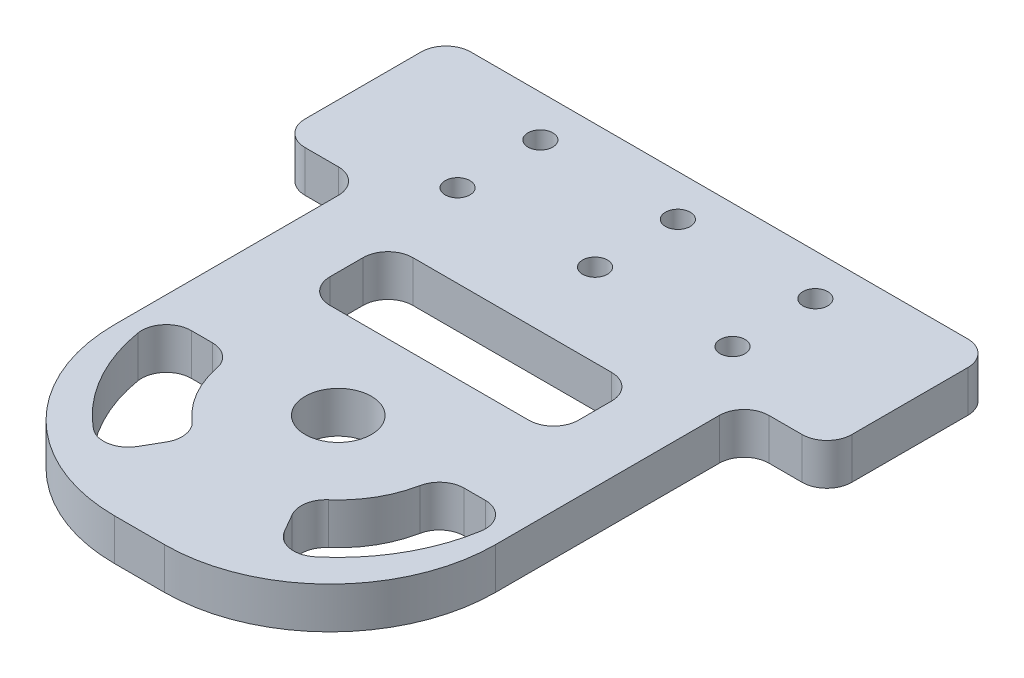
SolidWorks part; units mm, degrees
material "Thornel Mat VMA"
ref_plane "前视基准面" through (0, 0, 0) normal (0, 0, 1) x (1, 0, 0)
ref_plane "上视基准面" through (0, 0, 0) normal (0, 1, 0) x (1, 0, 0)
ref_plane "右视基准面" through (0, 0, 0) normal (1, 0, 0) x (0, 0, -1)
sketch "草图1" plane through (0, 0, 0) normal (0, 1, 0) x (1, 0, 0)
  line L1 (-23, -35) -> (23, -35)
  line L2 (-23, -35) -> (-23, 35)
  line L3 (-23, 35) -> (23, 35)
  line L4 (23, -35) -> (23, 35)
  line L5 (-23, -35) -> (23, 35) construction
  line L6 (-23, 35) -> (23, -35) construction
  point P0 (0, 0)
  dimension "D1" = 46
  dimension "D2" = 70
extrude "凸台-拉伸1" add sketch "草图1" along normal blind 5
sketch "草图2" plane through (0, 0, 0) normal (0, -1, 0) x (1, 0, 0)
  line L0 (23, -35) -> (-23, -35) construction
  circle A0 centre (0, 11) radius 4
  dimension "D2" = 8
  dimension "D1" = 46
extrude "切除-拉伸1" cut sketch "草图2" against normal through all
fillet "圆角1" radius 20 2 edges at (23, 2.5, 35) (-23, 2.5, 35)
sketch "草图6" plane through (0, 0, 0) normal (0, -1, 0) x (1, 0, 0)
  line L0 (23, -35) -> (-23, -35) construction
  line L7 (0, 7) -> (0, -35) construction
  line L8 (12.5, 11) -> (21, 11)
  line L9 (-12.5, 11) -> (-21, 11)
  line L10 (6.25, 21.8253) -> (10.5, 29.1865)
  line L11 (-6.25, 21.8253) -> (-10.5, 29.1865)
  circle A0 centre (0, 11) radius 4 construction
  arc A2 (12.5, 11) -> (6.25, 21.8253) centre (0, 11) ccw
  arc A3 (-6.25, 21.8253) -> (-12.5, 11) centre (0, 11) ccw
  arc A4 (21, 11) -> (10.5, 29.1865) centre (0, 11) ccw
  arc A5 (-10.5, 29.1865) -> (-21, 11) centre (0, 11) ccw
  point P0 (0, -14)
  dimension "D4" = 25
  dimension "D5" = 60
extrude "切除-拉伸4" cut sketch "草图6" against normal through all
fillet "圆角3" radius 3 8 edges at (21, 2.5, 11) (12.5, 2.5, 11) (6.25, 2.5, 21.8253) (10.5, 2.5, 29.1865) (-6.25, 2.5, 21.8253) (-10.5, 2.5, 29.1865) (-21, 2.5, 11) (-12.5, 2.5, 11)
sketch "草图8" plane through (23, 0, 0) normal (1, 0, 0) x (0, 0, -1)
  line L0 (-15, 5) -> (35, 5) construction
  line L1 (35, 0) -> (15, 0)
  line L2 (35, 0) -> (35, 5)
  line L3 (35, 5) -> (15, 5)
  line L4 (15, 0) -> (15, 5)
  dimension "D1" = 20
extrude "凸台-拉伸2" add sketch "草图8" along normal blind 10
sketch "草图9" plane through (-23, 0, 0) normal (-1, 0, 0) x (0, 0, 1)
  line L0 (-35, 5) -> (-35, 0) construction
  line L1 (-35, 5) -> (-15, 5)
  line L2 (-35, 5) -> (-35, 0)
  line L3 (-35, 0) -> (-15, 0)
  line L4 (-15, 5) -> (-15, 0)
  line L5 (-35, 5) -> (15, 5) construction
  line L6 (-35, 0) -> (15, 0) construction
  dimension "D1" = 20
extrude "凸台-拉伸3" add sketch "草图9" along normal blind 10
fillet "圆角6" radius 3 6 edges at (23, 2.5, -15) (33, 2.5, -35) (33, 2.5, -15) (-33, 2.5, -35) (-33, 2.5, -15) (-23, 2.5, -15)
sketch "草图10" plane through (0, 5, 0) normal (0, 1, 0) x (1, 0, 0)
  line L0 (-33, 25) -> (33, 25) construction
  line L1 (-33, 18) -> (-33, 32) construction
  line L2 (33, 32) -> (33, 18) construction
  line L3 (0, 35) -> (0, -35) construction
  line L4 (30, 35) -> (-30, 35) construction
  line L5 (-3, -35) -> (3, -35) construction
  line L7 (-16.6, 20) -> (16.6, 20) construction
  line L8 (-16.6, 20) -> (-16.6, 30) construction
  line L9 (-16.6, 30) -> (16.6, 30) construction
  line L10 (16.6, 20) -> (16.6, 30) construction
  line L11 (-16.6, 20) -> (16.6, 30) construction
  line L12 (-16.6, 30) -> (16.6, 20) construction
  circle A0 centre (-16.6, 30) radius 1.5
  circle A1 centre (0, 30) radius 1.5
  circle A2 centre (16.6, 30) radius 1.5
  circle A3 centre (16.6, 20) radius 1.5
  circle A4 centre (0, 20) radius 1.5
  circle A5 centre (-16.6, 20) radius 1.5
  point P12 (0, 25)
  point P21 (16.6, 30)
  dimension "D3" = 3
  dimension "D4" = 3
  dimension "D5" = 3
  dimension "D1" = 33.2
  dimension "D2" = 10
extrude "切除-拉伸5" cut sketch "草图10" against normal through all
sketch "草图11" plane through (0, 5, 0) normal (0, 1, 0) x (1, 0, 0)
  line L0 (0, -11) -> (0, 20) construction
  line L5 (30, 35) -> (-30, 35) construction
  line L6 (-15, 0) -> (15, 0)
  line L7 (-15, 0) -> (-15, 10)
  line L8 (-15, 10) -> (15, 10)
  line L9 (15, 0) -> (15, 10)
  line L10 (-15, 0) -> (15, 10) construction
  line L11 (-15, 10) -> (15, 0) construction
  point P0 (0, 5)
  dimension "D1" = 10
  dimension "D2" = 30
  dimension "D3" = 30
extrude "切除-拉伸6" cut sketch "草图11" against normal through all
fillet "圆角7" radius 3 4 edges at (-15, 2.5, -10) (15, 2.5, -10) (15, 2.5, 0) (-15, 2.5, 0)
